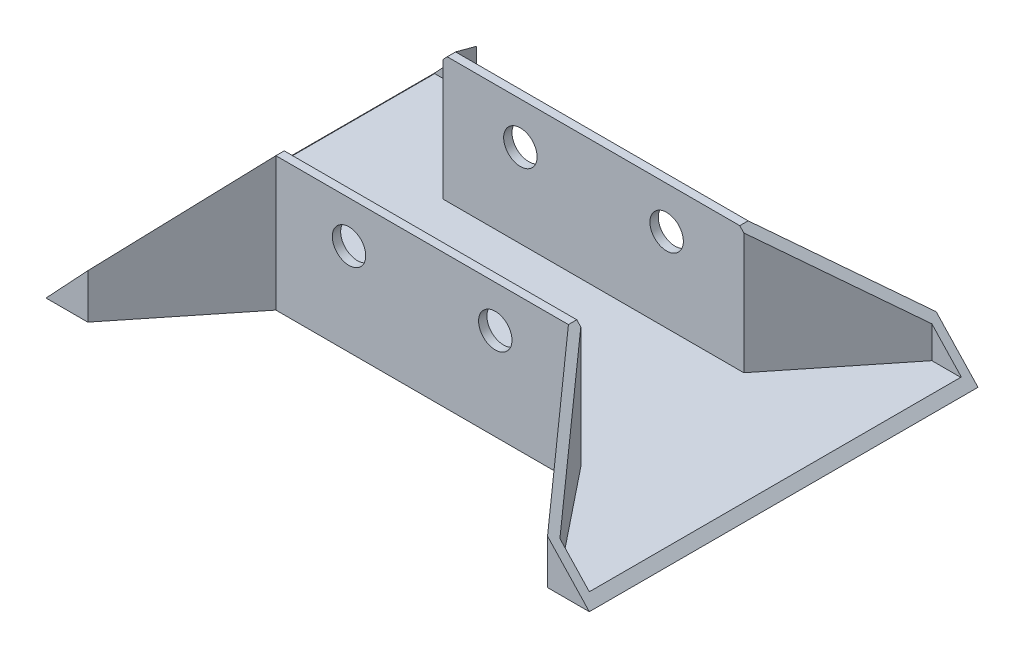
SolidWorks part; units mm, degrees
ref_plane "正面" through (0, 0, 0) normal (0, 0, 1) x (1, 0, 0)
ref_plane "平面" through (0, 0, 0) normal (0, 1, 0) x (1, 0, 0)
ref_plane "右側面" through (0, 0, 0) normal (1, 0, 0) x (0, 0, -1)
sketch "ｽｹｯﾁ1" plane through (0, 0, 0) normal (0, 0, 1) x (1, 0, 0)
  line L0 (-65, 0) -> (65, 0)
  line L1 (65, 0) -> (35, 32)
  line L2 (35, 32) -> (-35, 32)
  line L3 (-35, 32) -> (-65, 0)
  point P4 (0, 0)
  dimension "D1" = 130
  dimension "D2" = 30
  dimension "D3" = 30
  dimension "D4" = 32
extrude "ﾎﾞｽ - 押し出し1" add sketch "ｽｹｯﾁ1" along normal mid plane 93
sketch "ｽｹｯﾁ2" plane through (0, 32, 0) normal (0, 1, 0) x (1, 0, 0)
  line L0 (-55, -46.5) -> (-35, -21.5)
  line L2 (-35, -46.5) -> (-35, 46.5) construction
  line L3 (-35, -21.5) -> (35, -21.5)
  line L4 (35, -46.5) -> (35, 46.5) construction
  line L5 (35, -21.5) -> (55, -46.5)
  line L6 (65, -46.5) -> (35, -46.5) construction
  line L7 (55, -46.5) -> (-55, -46.5)
  line L8 (-55, 46.5) -> (-35, 21.5)
  line L9 (-35, 46.5) -> (-65, 46.5) construction
  line L10 (-35, 21.5) -> (35, 21.5)
  line L11 (35, 21.5) -> (55, 46.5)
  line L12 (65, 46.5) -> (35, 46.5) construction
  line L13 (55, 46.5) -> (-55, 46.5)
  line L14 (65, -46.5) -> (65, 46.5) construction
  line L15 (-65, -46.5) -> (-65, 46.5) construction
  line L16 (-35, -46.5) -> (-65, -46.5) construction
  dimension "D1" = 10
  dimension "D2" = 10
  dimension "D3" = 25
  dimension "D4" = 25
  dimension "D5" = 10
  dimension "D6" = 10
extrude "ｶｯﾄ - 押し出し1" cut sketch "ｽｹｯﾁ2" against normal through all
sketch "ｽｹｯﾁ3" plane through (0, 32, 0) normal (0, 1, 0) x (1, 0, 0)
  line L24 (-35.9612, -19.5) -> (35.9612, -19.5)
  line L25 (-55.9612, -44.5) -> (-35.9612, -19.5)
  line L26 (-63, -44.5) -> (-55.9612, -44.5)
  line L27 (-63, 44.5) -> (-63, -44.5)
  line L28 (-55.9612, 44.5) -> (-63, 44.5)
  line L29 (-35.9612, 19.5) -> (-55.9612, 44.5)
  line L30 (35.9612, 19.5) -> (-35.9612, 19.5)
  line L31 (55.9612, 44.5) -> (35.9612, 19.5)
  line L32 (63, 44.5) -> (55.9612, 44.5)
  line L33 (63, -44.5) -> (63, 44.5)
  line L34 (55.9612, -44.5) -> (63, -44.5)
  line L35 (35.9612, -19.5) -> (55.9612, -44.5)
  line L36 (-35.9612, -19.5) -> (35.9612, -19.5)
  line L37 (-55.9612, -44.5) -> (-35.9612, -19.5)
  line L38 (-63, -44.5) -> (-55.9612, -44.5)
  line L39 (-63, 44.5) -> (-63, -44.5)
  line L40 (-55.9612, 44.5) -> (-63, 44.5)
  line L41 (-35.9612, 19.5) -> (-55.9612, 44.5)
  line L42 (35.9612, 19.5) -> (-35.9612, 19.5)
  line L43 (55.9612, 44.5) -> (35.9612, 19.5)
  line L44 (63, 44.5) -> (55.9612, 44.5)
  line L45 (63, -44.5) -> (63, 44.5)
  line L46 (55.9612, -44.5) -> (63, -44.5)
  line L47 (35.9612, -19.5) -> (55.9612, -44.5)
  dimension "D1" = 2
extrude "ｶｯﾄ - 押し出し2" cut sketch "ｽｹｯﾁ3" against normal offset from surface (30 mm away) 2 up to face at (0, 0, 0)
sketch "ｽｹｯﾁ4" plane through (0, 0, 21.5) normal (0, 0, 1) x (1, 0, 0)
  line L0 (35, 32) -> (-35, 32) construction
  circle A0 centre (-17.5, 22) radius 4
  circle A1 centre (17.5, 22) radius 4
  dimension "D1" = 8
  dimension "D2" = 10
  dimension "D3" = 17.5
  dimension "D4" = 17.5
extrude "ｶｯﾄ - 押し出し3" cut sketch "ｽｹｯﾁ4" against normal through all
